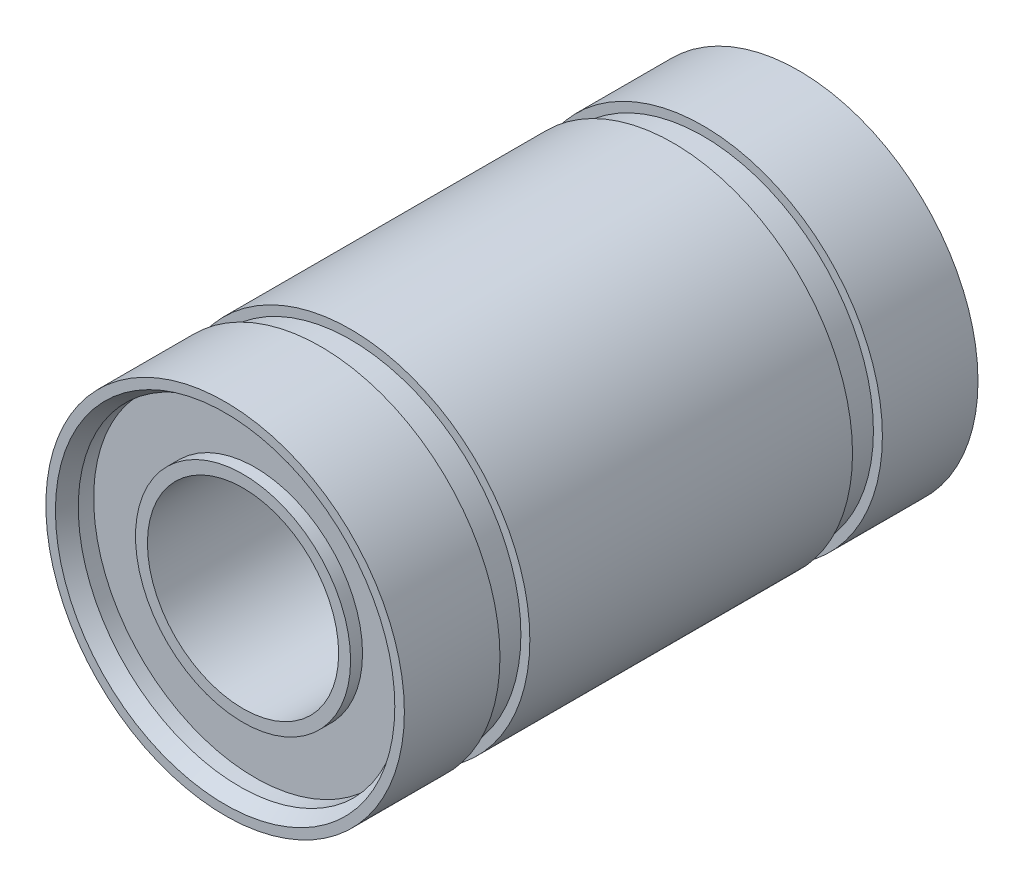
SolidWorks part; units mm, degrees
material "201 Stal nierdzewna odprężona (SS)"
ref_plane "Płaszczyzna przednia" through (0, 0, 0) normal (0, 0, 1) x (1, 0, 0)
ref_plane "Płaszczyzna górna" through (0, 0, 0) normal (0, 1, 0) x (1, 0, 0)
ref_plane "Płaszczyzna prawa" through (0, 0, 0) normal (1, 0, 0) x (0, 0, -1)
sketch "Szkic1" plane through (0, 0, 0) normal (0, 0, 1) x (1, 0, 0)
  circle A0 centre (0, 0) radius 7.5
  circle A1 centre (0, 0) radius 4
  dimension "D1" = 15
  dimension "D2" = 8
extrude "Dodanie-wyciągnięcie1" add sketch "Szkic1" along normal mid plane 24
sketch "Szkic2" plane through (0, 0, 12) normal (0, 0, 1) x (1, 0, 0)
  circle A0 centre (0, 0) radius 6.75
  dimension "D1" = 13.5
extrude "Wytnij-wyciągnięcie1" cut sketch "Szkic2" against normal blind 1.25
sketch "Szkic3" plane through (0, 0, 10.75) normal (0, 0, 1) x (1, 0, 0)
  circle A0 centre (0, 0) radius 4
  circle A1 centre (0, 0) radius 4.5
  circle A2 centre (0, 0) radius 4 construction
  dimension "D1" = 0.5
extrude "Dodanie-wyciągnięcie2" add sketch "Szkic3" along normal blind 0.5
chamfer "Sfazowanie1" distance 0.35 angle 60 1 edges at (6.75, 0, 12)
ref_plane "Płaszczyzna1" through (0, 0, 8) normal (0, 0, 1) x (1, 0, 0)
sketch "Szkic4" plane through (0, 0, 8) normal (0, 0, 1) x (1, 0, 0)
  circle A0 centre (0, 0) radius 7.5
  circle A1 centre (0, 0) radius 7.125
  circle A2 centre (0, 0) radius 7.5 construction
  dimension "D1" = 14.25
extrude "Wytnij-wyciągnięcie2" cut sketch "Szkic4" against normal blind 1.25
mirror "Lustro4" about plane through (0, 0, 0) normal (0, 0, 1) of "Wytnij-wyciągnięcie2", "Dodanie-wyciągnięcie2", "Wytnij-wyciągnięcie1"
chamfer "Sfazowanie2" distance 0.35 angle 60 1 edges at (6.75, 0, -12)
